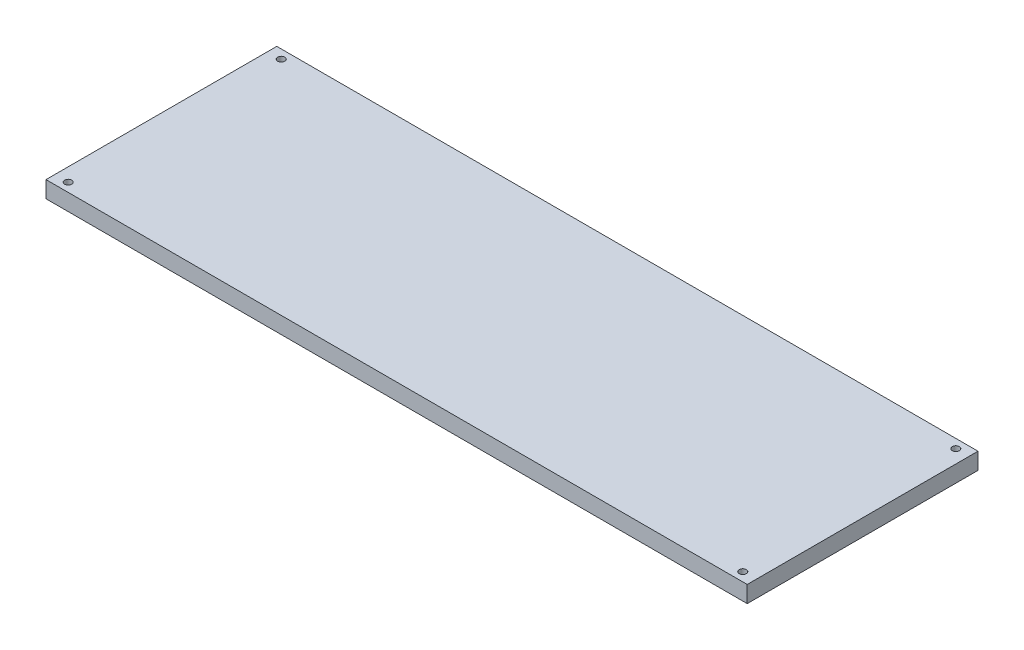
SolidWorks part; units mm, degrees
material "Pine"
ref_plane "Front Plane" through (0, 0, 0) normal (0, 0, 1) x (1, 0, 0)
ref_plane "Top Plane" through (0, 0, 0) normal (0, 1, 0) x (1, 0, 0)
ref_plane "Right Plane" through (0, 0, 0) normal (1, 0, 0) x (0, 0, -1)
sketch "Sketch1" plane through (0, 0, 0) normal (0, 1, 0) x (1, 0, 0)
  line L1 (-250.825, -82.55) -> (250.825, -82.55)
  line L2 (-250.825, -82.55) -> (-250.825, 82.55)
  line L3 (-250.825, 82.55) -> (250.825, 82.55)
  line L4 (250.825, -82.55) -> (250.825, 82.55)
  line L5 (-250.825, -82.55) -> (250.825, 82.55) construction
  line L6 (-250.825, 82.55) -> (250.825, -82.55) construction
  point P0 (0, 0)
  dimension "D1" = 501.65
  dimension "D2" = 165.1
extrude "Boss-Extrude1" add sketch "Sketch1" along normal blind 11.9062
hole_wizard "#7 (0.201) Diameter Hole1" positions "Sketch3" profile "Sketch4" hole size "#7" standard "ANSI Inch" end condition through all
sketch "Sketch3" plane through (0, 11.9062, 0) normal (0, 1, 0) x (1, 0, 0)
  line L0 (250.825, 82.55) -> (-250.825, 82.55) construction
  point P0 (-241.3, 76.2)
  point P12 (241.3, 76.2)
  point P13 (241.3, -76.2)
  point P19 (-241.3, -76.2)
  dimension "D1" = 6.35
  dimension "D2" = 241.3
  dimension "D5" = 152.4
  dimension "D6" = 482.6
  dimension "D3" = 2
  dimension "D4" = 2
sketch "Sketch4" plane through (-241.3, 11.9062, -76.2) normal (1, 0, 0) x (0, 0, 1)
  line L0 (0, 0) -> (0, 11.9062)
  line L1 (0, 11.9062) -> (2.5527, 11.9062)
  line L2 (2.5527, 11.9062) -> (2.5527, 0)
  line L5 (2.5527, 0) -> (0, 0)
  line L11 (0, -6.35) -> (0, 107.95) construction
  dimension "Thru Hole Dia." = 5.1054
  dimension "Thru Hole Depth" = 11.9062
